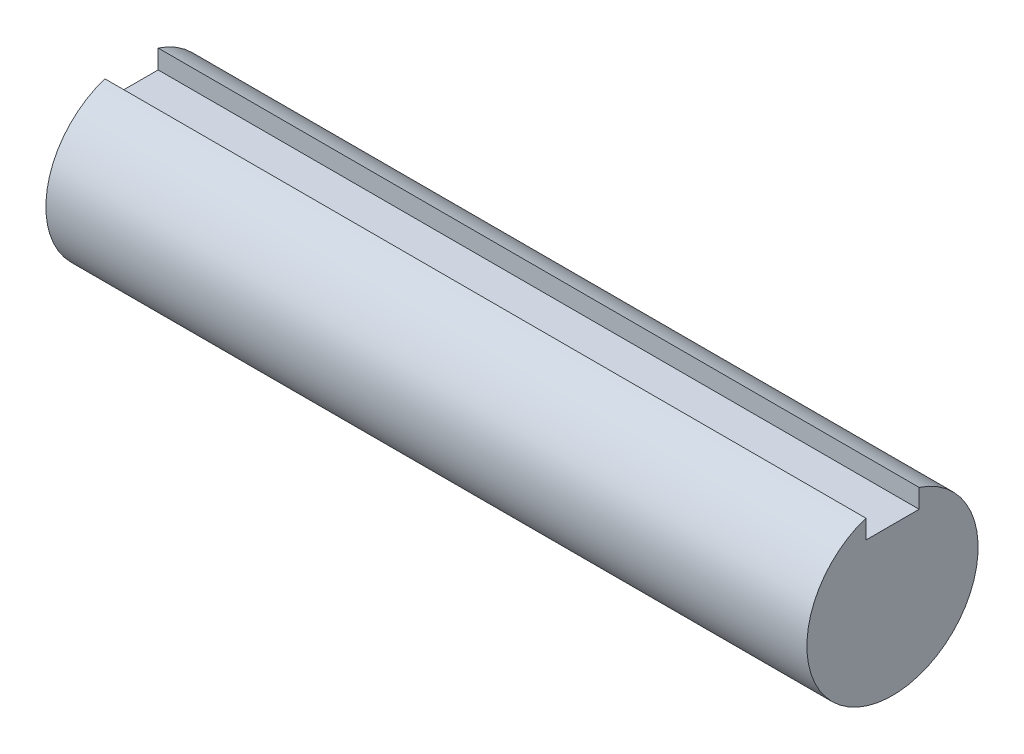
SolidWorks part; units mm, degrees
ref_plane "Front Plane" through (0, 0, 0) normal (0, 0, 1) x (1, 0, 0)
ref_plane "Top Plane" through (0, 0, 0) normal (0, 1, 0) x (1, 0, 0)
ref_plane "Right Plane" through (0, 0, 0) normal (1, 0, 0) x (0, 0, -1)
sketch "Sketch2" plane through (0, 0, 0) normal (1, 0, 0) x (0, 0, -1)
  line L0 (0, 82.8583) -> (0, 22.5) construction
  line L1 (-116.1143, 0) -> (118.3689, 0) construction
  line L3 (0, 16.4) -> (0, -93.286) construction
  line L5 (-7, 21.3834) -> (-7, 16.4)
  line L6 (-7, 16.4) -> (7, 16.4)
  line L7 (7, 21.3834) -> (7, 16.4)
  arc A0 (-7, 21.3834) -> (7, 21.3834) centre (0, 0) ccw
extrude "Boss-Extrude1" add sketch "Sketch2" along normal blind 200 contours A0 L7 L6 L5
